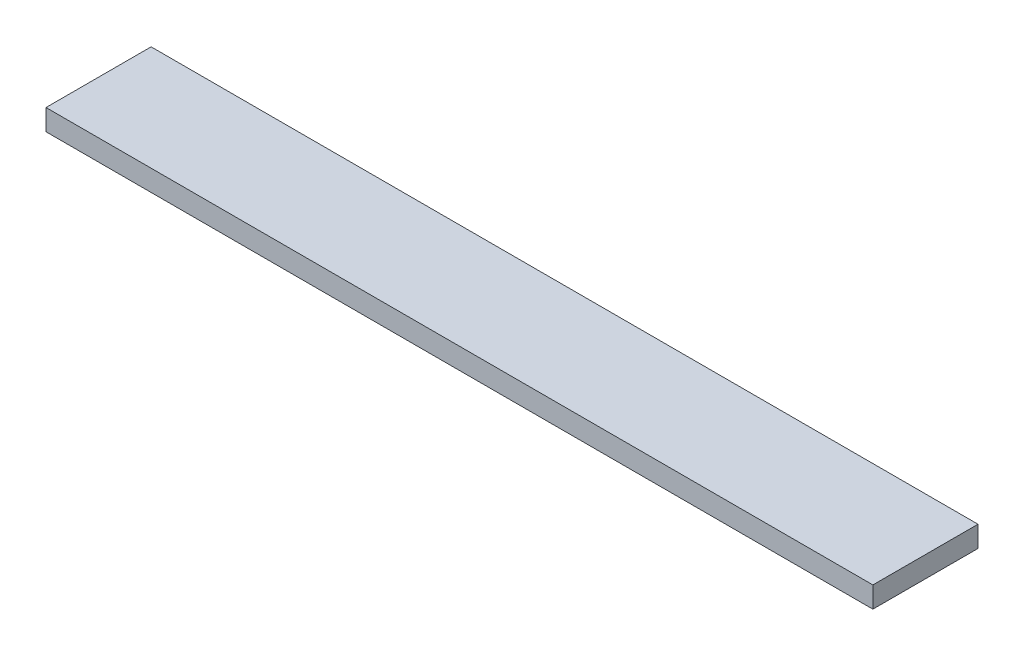
SolidWorks part; units mm, degrees
material "Hêtre"
ref_plane "Plan de face" through (0, 0, 0) normal (0, 0, 1) x (1, 0, 0)
ref_plane "Plan de dessus" through (0, 0, 0) normal (0, 1, 0) x (1, 0, 0)
ref_plane "Plan de droite" through (0, 0, 0) normal (1, 0, 0) x (0, 0, -1)
sketch "Esquisse1" plane through (0, 0, 0) normal (0, 0, 1) x (1, 0, 0)
  line L0 (0, 0) -> (0, 30)
  line L1 (0, 30) -> (1180, 30)
  line L2 (1180, 30) -> (1180, 0)
  line L3 (1180, 0) -> (0, 0)
  dimension "D1" = 30
  dimension "D2" = 1180
extrude "Boss.-Extru.1" add sketch "Esquisse1" along normal blind 150
